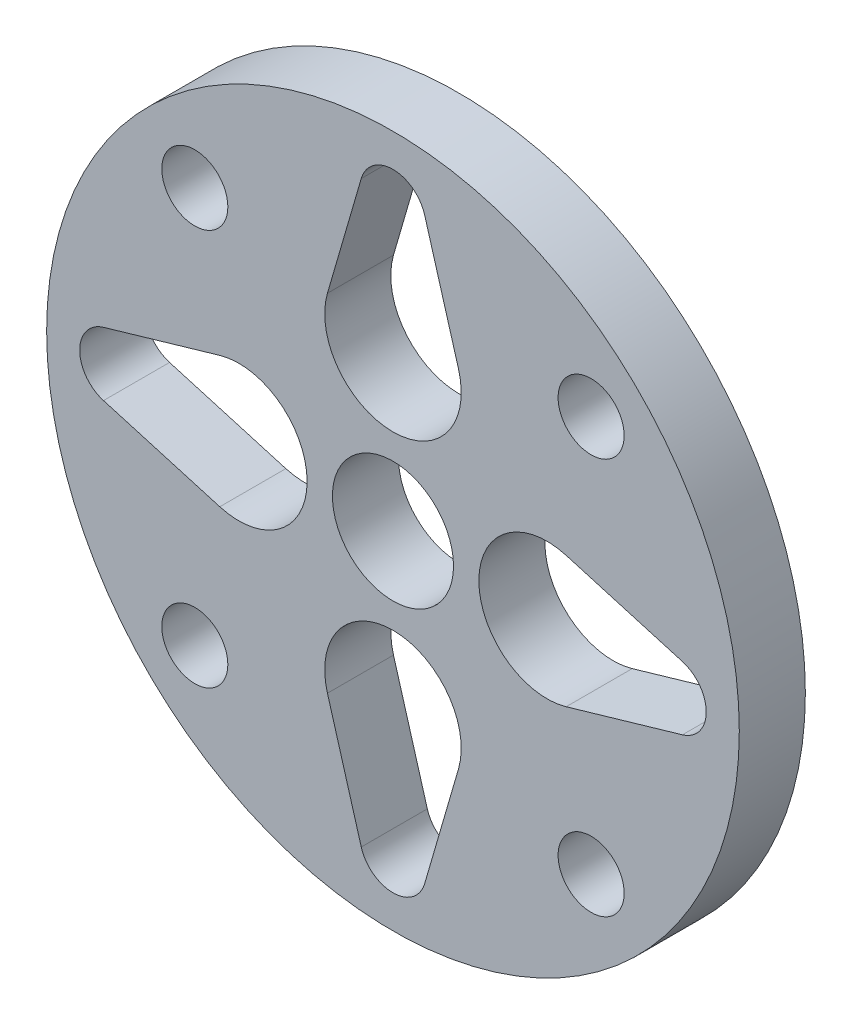
SolidWorks part; units mm, degrees
ref_plane "Alzado" through (0, 0, 0) normal (0, 0, 1) x (1, 0, 0)
ref_plane "Planta" through (0, 0, 0) normal (0, 1, 0) x (1, 0, 0)
ref_plane "Vista lateral" through (0, 0, 0) normal (1, 0, 0) x (0, 0, -1)
sketch "Model" plane through (0, 0, 0) normal (0, 0, 1) x (1, 0, 0)
  line L0 (23.9085, 297.8774) -> (25.4448, 292.5964)
  line L1 (21.0279, 297.8774) -> (19.4916, 292.5964)
  line L2 (9.3213, 286.1707) -> (14.6022, 287.707)
  line L3 (9.3213, 283.2902) -> (14.6022, 281.7538)
  line L4 (21.0279, 271.5835) -> (19.4916, 276.8645)
  line L5 (23.9085, 271.5835) -> (25.4448, 276.8645)
  line L6 (35.6151, 283.2902) -> (30.3341, 281.7538)
  line L7 (35.6151, 286.1707) -> (30.3341, 287.707)
  arc A0 (19.4916, 292.5964) -> (25.4448, 292.5964) centre (22.4682, 291.7304) ccw
  arc A1 (14.6022, 281.7538) -> (14.6022, 287.707) centre (15.4682, 284.7304) ccw
  arc A2 (25.4448, 276.8645) -> (19.4916, 276.8645) centre (22.4682, 277.7304) ccw
  arc A3 (30.3341, 287.707) -> (30.3341, 281.7538) centre (29.4682, 284.7304) ccw
  arc A4 (23.9085, 297.8774) -> (21.0279, 297.8774) centre (22.4682, 297.4584) ccw
  arc A5 (9.3213, 286.1707) -> (9.3213, 283.2902) centre (9.7403, 284.7304) ccw
  arc A6 (21.0279, 271.5835) -> (23.9085, 271.5835) centre (22.4682, 272.0025) ccw
  arc A7 (35.6151, 283.2902) -> (35.6151, 286.1707) centre (35.1961, 284.7304) ccw
  circle A8 centre (22.4682, 284.7304) radius 15.73
  circle A9 centre (13.4682, 275.7304) radius 1.5
  circle A10 centre (31.4682, 275.7304) radius 1.5
  circle A11 centre (31.4682, 293.7304) radius 1.5
  circle A12 centre (13.4682, 293.7304) radius 1.5
  circle A13 centre (22.4682, 284.7304) radius 2.75
extrude "Saliente-Extruir1" add sketch "Model" along normal blind 3
